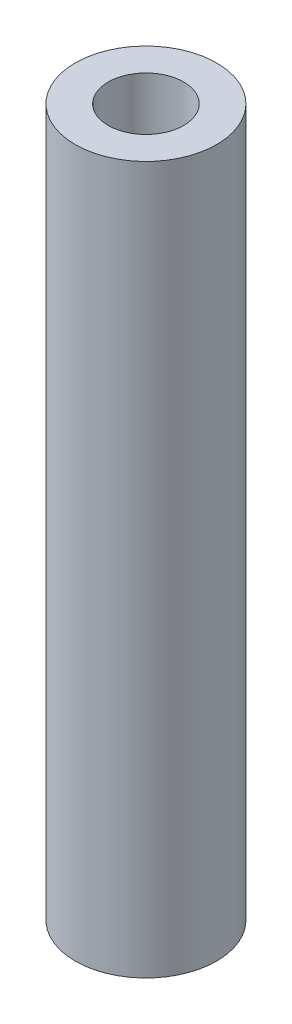
SolidWorks part; units mm, degrees
ref_plane "Front Plane" through (0, 0, 0) normal (0, 0, 1) x (1, 0, 0)
ref_plane "Top Plane" through (0, 0, 0) normal (0, 1, 0) x (1, 0, 0)
ref_plane "Right Plane" through (0, 0, 0) normal (1, 0, 0) x (0, 0, -1)
sketch "Sketch1" plane through (0, 0, 0) normal (0, 1, 0) x (1, 0, 0)
  circle A0 centre (0, 0) radius 1.6
  circle A1 centre (0, 0) radius 3
  dimension "D1" = 3.2
  dimension "D2" = 6
extrude "Boss-Extrude1" add sketch "Sketch1" along normal blind 30
